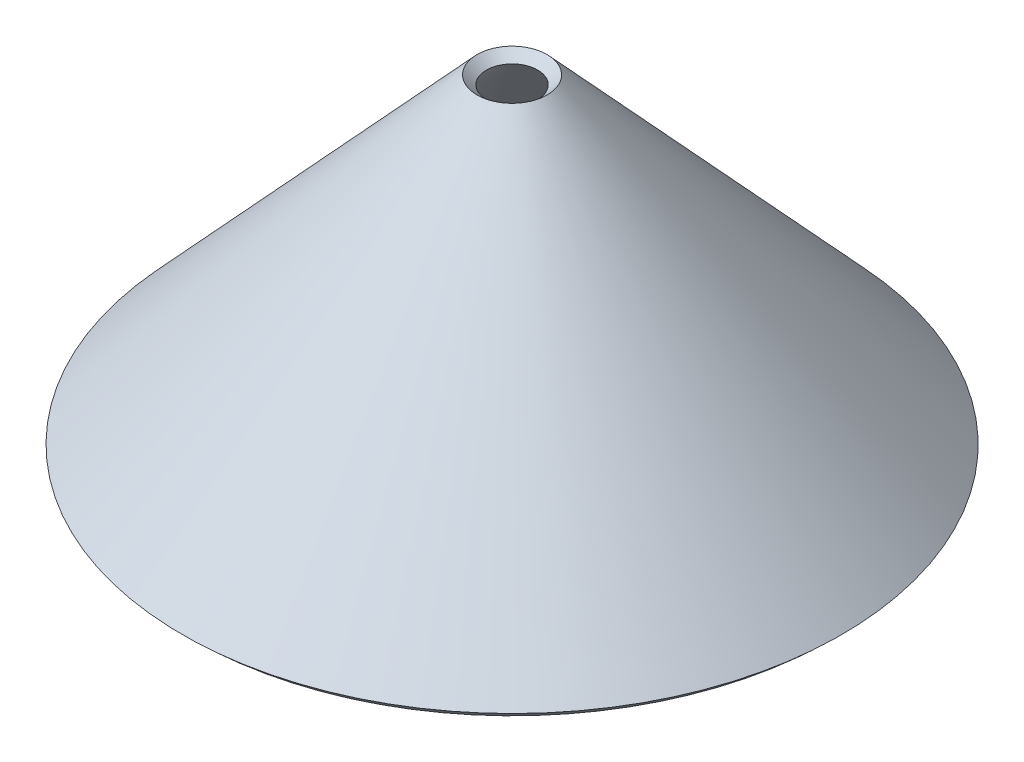
SolidWorks part; units mm, degrees
ref_plane "Front Plane" through (0, 0, 0) normal (0, 0, 1) x (1, 0, 0)
ref_plane "Top Plane" through (0, 0, 0) normal (0, 1, 0) x (1, 0, 0)
ref_plane "Right Plane" through (0, 0, 0) normal (1, 0, 0) x (0, 0, -1)
sketch "Sketch1" plane through (0, 0, 0) normal (1, 0, 0) x (0, 0, -1)
  line L0 (0, 0) -> (0, -635)
  line L2 (-50.8, 0) -> (-635, -635)
  dimension "D1" = 50.8
  dimension "D2" = 635
  dimension "D3" = 635
revolve "Revolve-Thin2" add sketch "Sketch1" angle 360 about L0
sketch "Sketch2" plane through (0, 0, 0) normal (1, 0, 0) x (0, 0, -1)
  line L0 (-653.6926, -617.8028) -> (653.6926, -617.8028)
